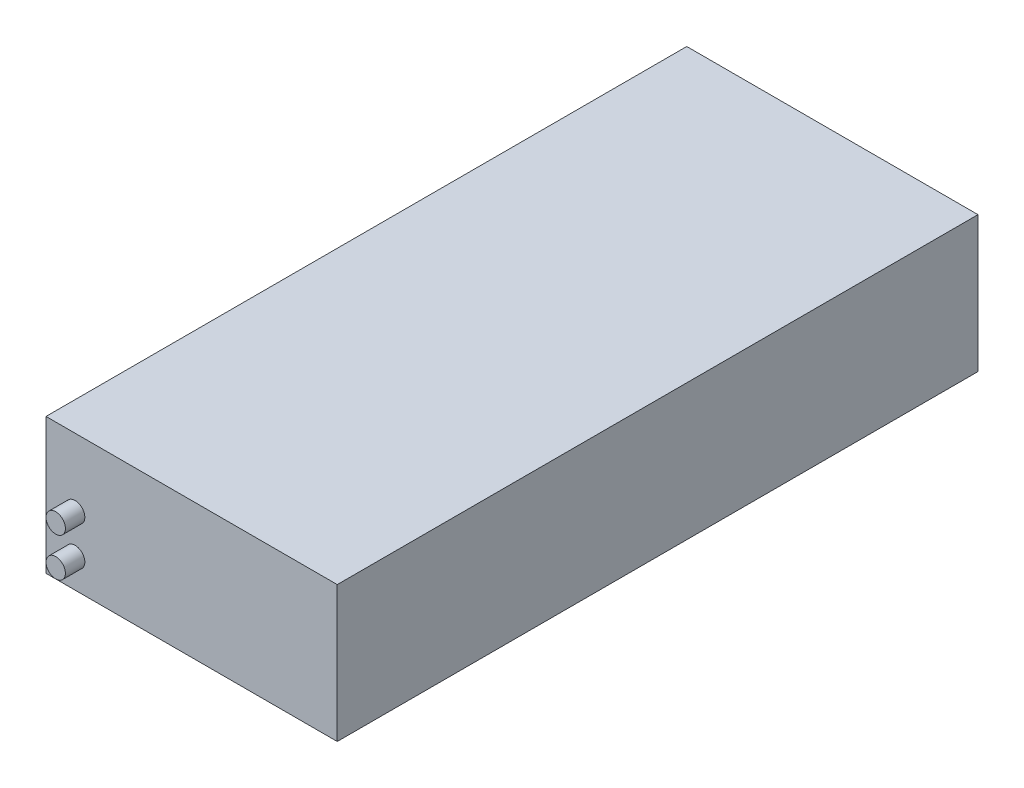
SolidWorks part; units mm, degrees
ref_plane "前视基准面" through (0, 0, 0) normal (0, 0, 1) x (1, 0, 0)
ref_plane "上视基准面" through (0, 0, 0) normal (0, 1, 0) x (1, 0, 0)
ref_plane "右视基准面" through (0, 0, 0) normal (1, 0, 0) x (0, 0, -1)
sketch "草图1" plane through (0, 0, 0) normal (0, 0, 1) x (1, 0, 0)
  line L1 (-75, 35) -> (75, 35)
  line L2 (-75, 35) -> (-75, -35)
  line L3 (-75, -35) -> (75, -35)
  line L4 (75, 35) -> (75, -35)
  line L5 (0, -35) -> (0, 35) construction
  line L6 (-75, 0) -> (75, 0) construction
  point P0 (0, 0)
  dimension "D1" = 70
  dimension "D2" = 150
extrude "凸台-拉伸1" add sketch "草图1" along normal blind 330
sketch "草图2" plane through (0, 0, 330) normal (0, 0, 1) x (1, 0, 0)
  line L0 (-60, -40.3782) -> (-60, 49959.6218) construction
  line L5 (-75, 35) -> (-75, -35) construction
  line L6 (-75, -35) -> (75, -35) construction
  circle A0 centre (-60, 0) radius 5
  circle A1 centre (-60, -20) radius 5
  point P4 (-91.7554, -40.5191)
  dimension "D2" = 10
  dimension "D3" = 10
  dimension "D4" = 20
  dimension "D5" = 15
  dimension "D1" = 15
extrude "凸台-拉伸2" add sketch "草图2" along normal blind 10
